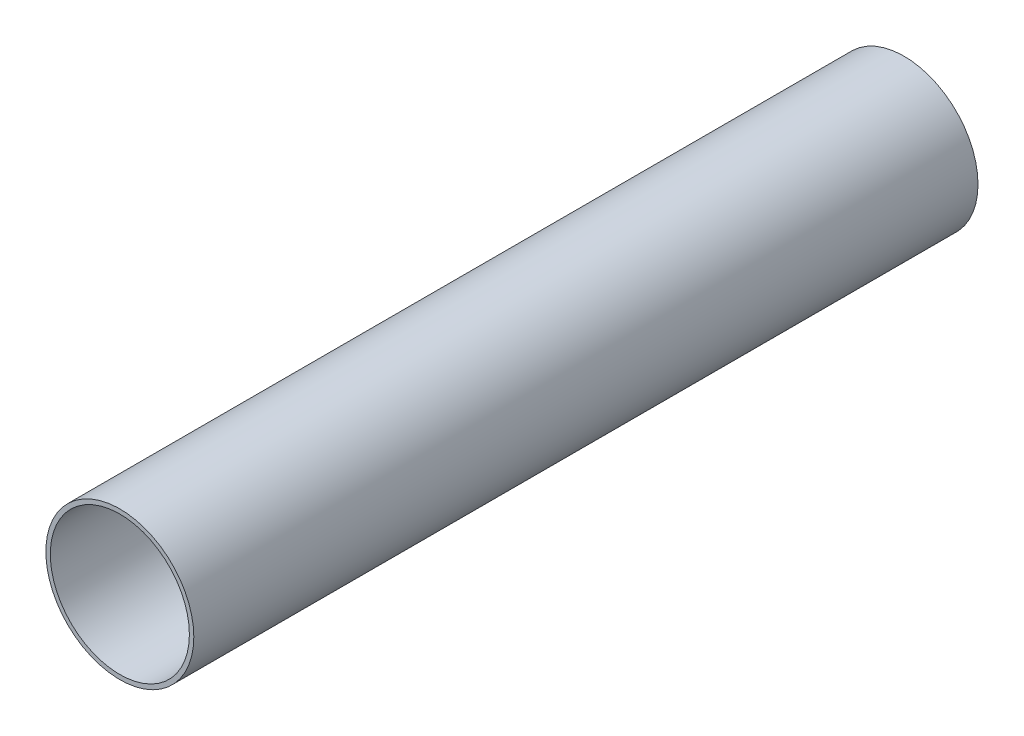
SolidWorks part; units mm, degrees
ref_plane "Front Plane" through (0, 0, 0) normal (0, 0, 1) x (1, 0, 0)
ref_plane "Top Plane" through (0, 0, 0) normal (0, 1, 0) x (1, 0, 0)
ref_plane "Right Plane" through (0, 0, 0) normal (1, 0, 0) x (0, 0, -1)
sketch "Sketch1" plane through (0, 0, 0) normal (0, 0, 1) x (1, 0, 0)
  circle A0 centre (0, 0) radius 50
  circle A1 centre (0, 0) radius 47
  dimension "D1" = 100
  dimension "D2" = 94
extrude "Boss-Extrude1" add sketch "Sketch1" along normal blind 530
sketch "Sketch2" plane through (0, 0, 0) normal (0, 1, 0) x (1, 0, 0)
  circle A0 centre (0, -120) radius 34
  circle A1 centre (0, -330) radius 34
  dimension "D1" = 68
  dimension "D2" = 68
  dimension "D3" = 120
  dimension "D4" = 210
extrude "Cut-Extrude1" cut sketch "Sketch2" against normal blind 500
